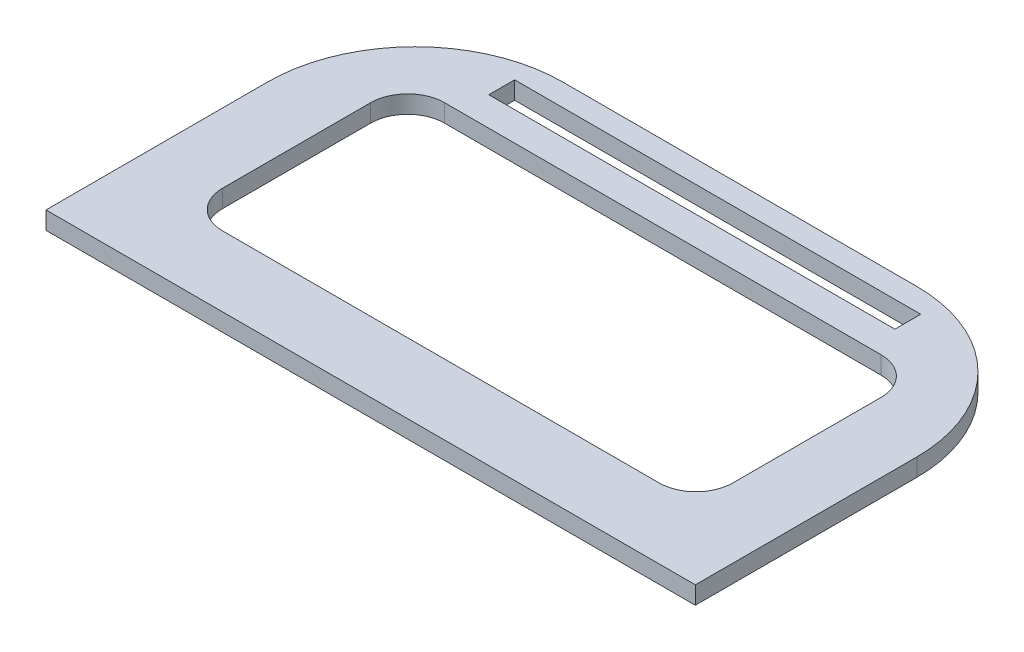
SolidWorks part; units mm, degrees
material "PBT General Purpose"
ref_plane "Front Plane" through (0, 0, 0) normal (0, 0, 1) x (1, 0, 0)
ref_plane "Top Plane" through (0, 0, 0) normal (0, 1, 0) x (1, 0, 0)
ref_plane "Right Plane" through (0, 0, 0) normal (1, 0, 0) x (0, 0, -1)
sketch "Sketch1" plane through (0, 0, 0) normal (0, 1, 0) x (1, 0, 0)
  line L0 (0, 0) -> (0, 5)
  line L1 (0, 5) -> (8.7951, 5)
  line L2 (8.7951, 5) -> (8.7951, 0)
  line L3 (8.7951, 0) -> (0, 0)
  line L4 (1.6475, 4.7) -> (1.6475, 4.35)
  line L5 (1.6475, 4.35) -> (7.1475, 4.35)
  line L6 (7.1475, 4.35) -> (7.1475, 4.7)
  line L7 (7.1475, 4.7) -> (1.6475, 4.7)
  point P7 (4.3975, 4.7)
  point P10 (4.3975, 5)
  dimension "D1" = 5.5
  dimension "D2" = 5
  dimension "D3" = 0.35
  dimension "D8" = 0.3
extrude "Boss-Extrude1" add sketch "Sketch1" along normal blind 0.24
fillet "Fillet1" radius 2 2 edges at (8.7951, 0.12, -5) (0, 0.12, -5)
sketch "Sketch2" plane through (0, 0.24, 0) normal (0, 1, 0) x (1, 0, 0)
  line L0 (0, 0) -> (8.7951, 0) construction
  line L1 (0.9409, 3.9569) -> (7.8542, 3.9569)
  line L2 (0.9409, 3.9569) -> (0.9409, 0.9497)
  line L3 (0.9409, 0.9497) -> (7.8542, 0.9497)
  line L4 (7.8542, 3.9569) -> (7.8542, 0.9497)
  point P4 (4.3975, 0.9497)
  point P7 (4.3975, 0)
extrude "Cut-Extrude1" cut sketch "Sketch2" against normal through all
fillet "Fillet4" radius 0.5 4 edges at (7.8542, 0.12, -0.9497) (7.8542, 0.12, -3.9569) (0.9409, 0.12, -3.9569) (0.9409, 0.12, -0.9497)
